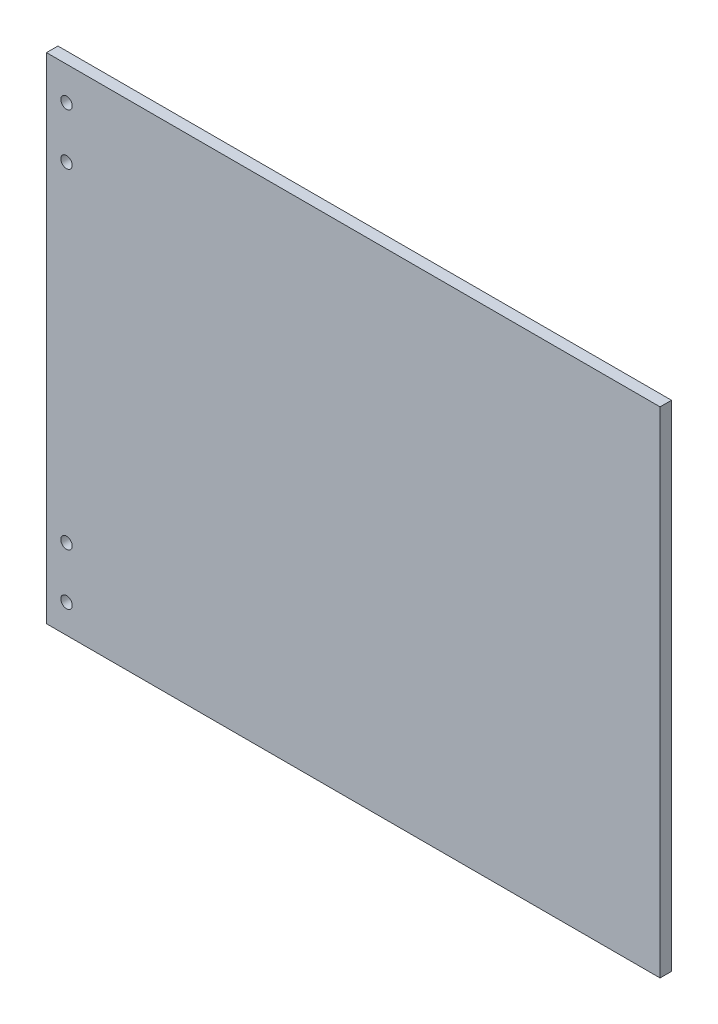
SolidWorks part; units mm, degrees
ref_plane "Plan de face" through (0, 0, 0) normal (0, 0, 1) x (1, 0, 0)
ref_plane "Plan de dessus" through (0, 0, 0) normal (0, 1, 0) x (1, 0, 0)
ref_plane "Plan de droite" through (0, 0, 0) normal (1, 0, 0) x (0, 0, -1)
sketch "Esquisse1" plane through (0, 0, 0) normal (0, 0, 1) x (1, 0, 0)
  line L1 (-5.9446, -5.9446) -> (316.0554, -5.9446)
  line L2 (-5.9446, -5.9446) -> (-5.9446, 253.6369)
  line L3 (-5.9446, 253.6369) -> (316.0554, 253.6369)
  line L4 (316.0554, -5.9446) -> (316.0554, 253.6369)
  dimension "D1" = 322
extrude "Boss.-Extru.1" add sketch "Esquisse1" along normal blind 6
sketch "Esquisse2" plane through (0, 0, 0) normal (0, 0, -1) x (-1, 0, 0)
  circle A0 centre (-4.5554, 236.1369) radius 3
  circle A1 centre (-4.5554, 209.1369) radius 3
  circle A2 centre (-4.5554, 36.1369) radius 3
  circle A3 centre (-4.5554, 9.1369) radius 3
  dimension "D1" = 6
extrude "Enlèv. mat.-Extru.1" cut sketch "Esquisse2" against normal up to next
